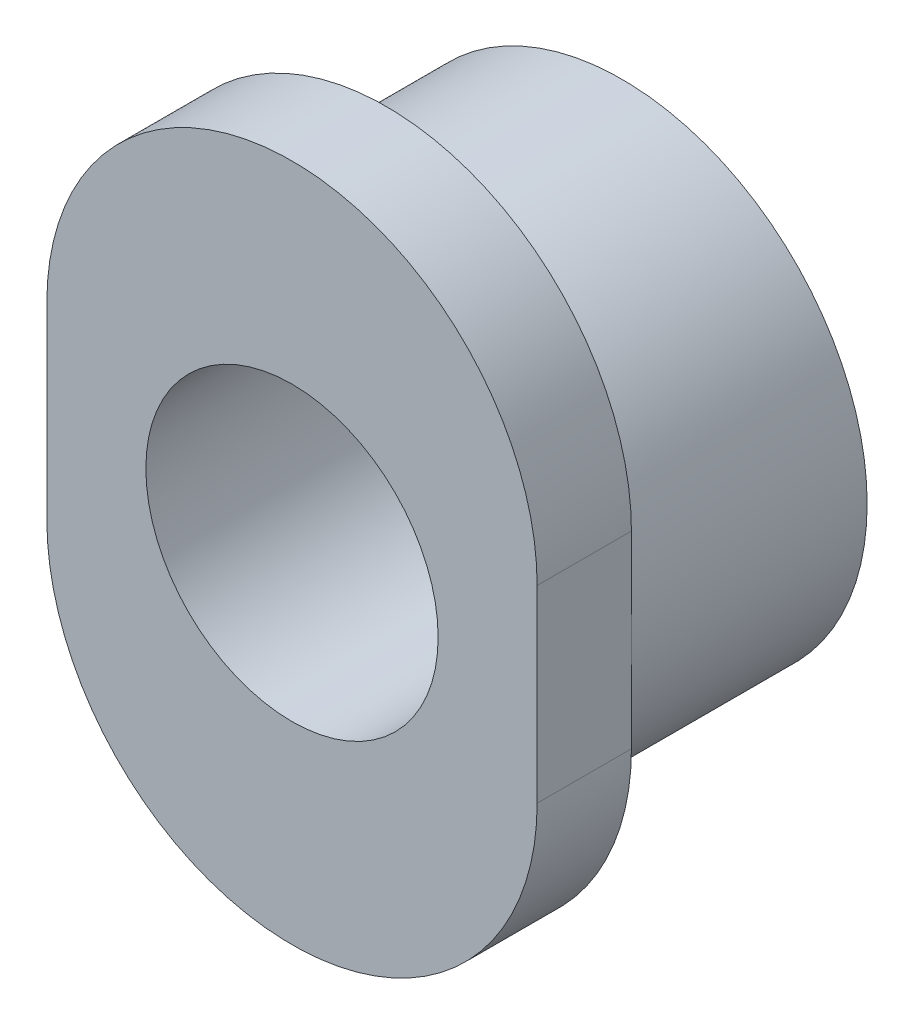
SolidWorks part; units mm, degrees
ref_plane "Płaszczyzna przednia" through (0, 0, 0) normal (0, 0, 1) x (1, 0, 0)
ref_plane "Płaszczyzna górna" through (0, 0, 0) normal (0, 1, 0) x (1, 0, 0)
ref_plane "Płaszczyzna prawa" through (0, 0, 0) normal (1, 0, 0) x (0, 0, -1)
sketch "Szkic1" plane through (0, 0, 0) normal (0, 0, 1) x (1, 0, 0)
  circle A0 centre (0, 0) radius 2.6
  circle A1 centre (0, 0) radius 1.55
  dimension "D1" = 3.1
  dimension "D2" = 5.2
extrude "Dodanie-wyciągnięcie1" add sketch "Szkic1" along normal blind 2.5
sketch "Szkic2" plane through (0, 0, 2.5) normal (0, 0, 1) x (1, 0, 0)
  line L0 (0, -1) -> (0, 1) construction
  line L1 (-2.6, -1) -> (-2.6, 1)
  line L2 (2.6, -1) -> (2.6, 1)
  arc A0 (-2.6, -1) -> (2.6, -1) centre (0, -1) ccw
  arc A1 (2.6, 1) -> (-2.6, 1) centre (0, 1) ccw
  circle A2 centre (0, 0) radius 1.55
  circle A3 centre (0, 0) radius 1.55 construction
  circle A4 centre (0, 0) radius 2.6 construction
  point P2 (0, 0)
  dimension "D1" = 2
extrude "Dodanie-wyciągnięcie2" add sketch "Szkic2" along normal blind 1
